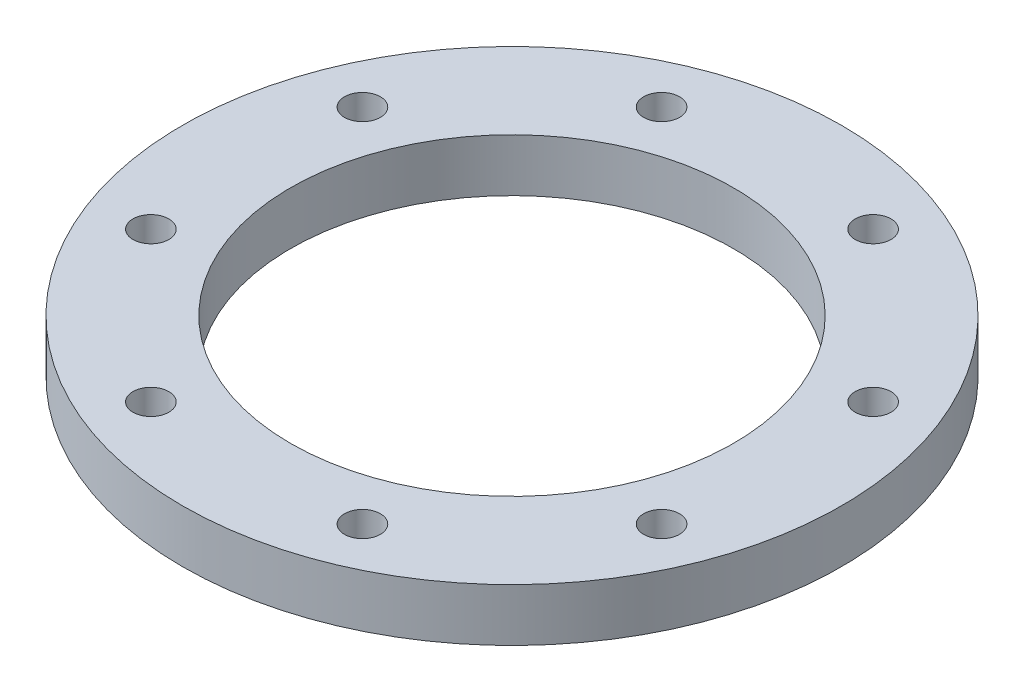
SolidWorks part; units mm, degrees
ref_plane "Płaszczyzna przednia" through (0, 0, 0) normal (0, 0, 1) x (1, 0, 0)
ref_plane "Płaszczyzna górna" through (0, 0, 0) normal (0, 1, 0) x (1, 0, 0)
ref_plane "Płaszczyzna prawa" through (0, 0, 0) normal (1, 0, 0) x (0, 0, -1)
sketch "Szkic1" plane through (0, 0, 0) normal (0, 0, 1) x (1, 0, 0)
  line L0 (0, 12.1549) -> (0, -6.619) construction
  line L1 (-42, 3.381) -> (-42, -6.619)
  line L2 (-62.5, 3.381) -> (-62.5, -6.619)
  line L3 (-42, 3.381) -> (-62.5, 3.381)
  line L4 (-62.5, -6.619) -> (-42, -6.619)
  dimension "D1" = 42
  dimension "D2" = 62.5
  dimension "D3" = 10
revolve "Obrót1" add sketch "Szkic1" angle 360 about L0
cosmetic thread "Oznaczenie gwintu1" parameters "D1"=10, "D2"=119
ref_plane "Płaszczyzna1" through (0, 3.381, 0) normal (0, 1, 0) x (1, 0, 0)
sketch "Szkic2" plane through (0, 3.381, 0) normal (0, 1, 0) x (1, 0, 0)
  line L0 (0, 0) -> (96.4385, 0) construction
  line L1 (48.4258, -20.0586) -> (48.4258, 20.0586)
  line L2 (48.4258, 20.0586) -> (20.0586, 48.4258)
  line L3 (20.0586, 48.4258) -> (-20.0586, 48.4258)
  line L4 (-20.0586, 48.4258) -> (-48.4258, 20.0586)
  line L5 (-48.4258, 20.0586) -> (-48.4258, -20.0586)
  line L6 (-48.4258, -20.0586) -> (-20.0586, -48.4258)
  line L7 (-20.0586, -48.4258) -> (20.0586, -48.4258)
  line L8 (20.0586, -48.4258) -> (48.4258, -20.0586)
  line L9 (0, 0) -> (48.4258, -20.0586)
  circle A0 centre (0, 0) radius 48.4258 construction
  dimension "D1" = 22.5
hole_wizard "Otwór gwintowany M81" positions "Szkic 3D1" profile "Szkic3" hole size "M8" standard "ISO" end condition through all
sketch3d "Szkic 3D1"
  point P0 (-20.0586, 3.381, -48.4258)
  point P3 (20.0586, 3.381, -48.4258)
  point P6 (48.4258, 3.381, -20.0586)
  point P9 (48.4258, 3.381, 20.0586)
  point P12 (20.0586, 3.381, 48.4258)
  point P15 (-20.0586, 3.381, 48.4258)
  point P18 (-48.4258, 3.381, 20.0586)
  point P21 (-48.4258, 3.381, -20.0586)
sketch "Szkic3" plane through (-20.0586, 3.381, -48.4258) normal (1, 0, 0) x (0, 0, 1)
  line L0 (0, 0) -> (0, 10)
  line L1 (0, 10) -> (3.4, 10)
  line L2 (3.4, 10) -> (3.4, 0)
  line L5 (3.4, 0) -> (0, 0)
  line L11 (0, -6.35) -> (0, 107.95) construction
  dimension "Średnica otworu na wylot" = 6.8
  dimension "Głębokość otworu na wylot" = 10
